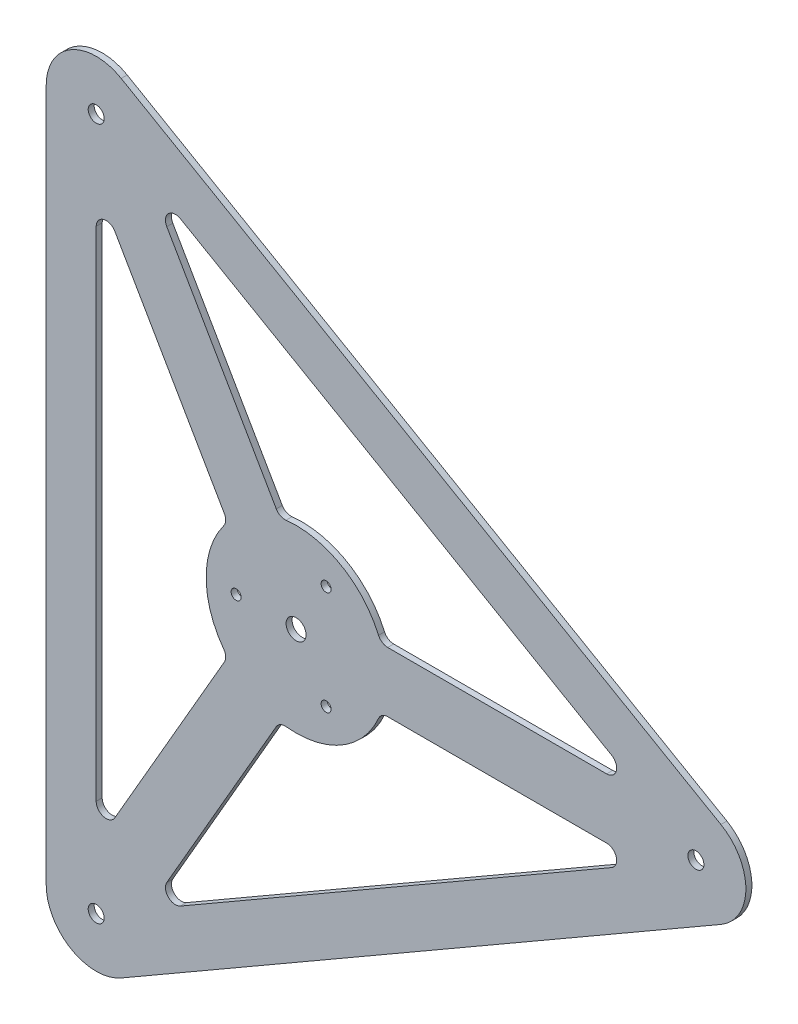
SolidWorks part; units mm, degrees
material "Hexcel AS4C (3000 Filaments)"
ref_plane "Front" through (0, 0, 0) normal (0, 0, 1) x (1, 0, 0)
ref_plane "Top" through (0, 0, 0) normal (0, 1, 0) x (1, 0, 0)
ref_plane "Right" through (0, 0, 0) normal (1, 0, 0) x (0, 0, -1)
sketch "BoardSke" plane through (0, 0, 0) normal (0, 0, 1) x (1, 0, 0)
  line L1 (42.5, 4.3301) -> (-17.5, 38.9711)
  line L2 (-25, 34.641) -> (-25, -34.641)
  line L3 (-17.5, -38.9711) -> (42.5, -4.3301)
  circle A0 centre (0, 0) radius 25 construction
  arc A1 (-25, -34.641) -> (-17.5, -38.9711) centre (-20, -34.641) ccw
  arc A2 (42.5, 4.3301) -> (42.5, -4.3301) centre (40, 0) cw
  arc A3 (-17.5, 38.9711) -> (-25, 34.641) centre (-20, 34.641) ccw
  dimension "D1" = 50
  dimension "D2" = 5
extrude "Board" add sketch "BoardSke" along normal blind 0.6 separate body
sketch "CutSke" plane through (0, 0, 0.6) normal (0, 0, 1) x (1, 0, 0)
  line L0 (31.0718, 3) -> (9.1652, 3)
  line L1 (31.5718, 4.866) -> (-11.5718, 29.775)
  line L2 (-12.9378, 28.409) -> (-1.9845, 9.4373)
  line L3 (0, 0) -> (-22.5, 38.9711) construction
  line L4 (0, 0) -> (45, 0) construction
  line L5 (0, 0) -> (-22.5, -38.9711) construction
  line L6 (42.5, 4.3301) -> (-17.5, 38.9711) construction
  line L7 (31.0718, -3) -> (9.1652, -3)
  line L8 (-11.5718, -29.775) -> (31.5718, -4.866)
  line L9 (-12.9378, -28.409) -> (-1.9845, -9.4373)
  line L10 (-18.134, -25.409) -> (-7.1807, -6.4373)
  line L11 (-20, 24.909) -> (-20, -24.909)
  line L12 (-18.134, 25.409) -> (-7.1807, 6.4373)
  arc A0 (8.2486, 3.6) -> (-1.0066, 8.9435) centre (0, 0) ccw
  arc A1 (-17.5, 38.9711) -> (-25, 34.641) centre (-20, 34.641) ccw construction
  arc A2 (42.5, -4.3301) -> (42.5, 4.3301) centre (40, 0) ccw construction
  arc A3 (-25, -34.641) -> (-17.5, -38.9711) centre (-20, -34.641) ccw construction
  arc A4 (31.0718, 3) -> (31.5718, 4.866) centre (31.0718, 4) ccw
  arc A5 (-11.5718, 29.775) -> (-12.9378, 28.409) centre (-12.0718, 28.909) ccw
  arc A6 (-1.9845, 9.4373) -> (-1.0066, 8.9435) centre (-1.1185, 9.9373) ccw
  arc A7 (9.1652, 3) -> (8.2486, 3.6) centre (9.1652, 4) cw
  arc A8 (-1.0066, -8.9435) -> (8.2486, -3.6) centre (0, 0) ccw
  arc A9 (-1.9845, -9.4373) -> (-1.0066, -8.9435) centre (-1.1185, -9.9373) cw
  arc A10 (9.1652, -3) -> (8.2486, -3.6) centre (9.1652, -4) ccw
  arc A11 (31.5718, -4.866) -> (31.0718, -3) centre (31.0718, -4) ccw
  arc A12 (-12.9378, -28.409) -> (-11.5718, -29.775) centre (-12.0718, -28.909) ccw
  arc A13 (-7.242, 5.3435) -> (-7.242, -5.3435) centre (0, 0) ccw
  arc A14 (-7.1807, 6.4373) -> (-7.242, 5.3435) centre (-8.0467, 5.9373) cw
  arc A15 (-7.1807, -6.4373) -> (-7.242, -5.3435) centre (-8.0467, -5.9373) ccw
  arc A16 (-20, -24.909) -> (-18.134, -25.409) centre (-19, -24.909) ccw
  arc A17 (-18.134, 25.409) -> (-20, 24.909) centre (-19, 24.909) ccw
  point P55 (0, 0)
  dimension "D1" = 18
  dimension "D5" = 1
  dimension "D6" = 1
  dimension "D2" = 3
  dimension "D3" = 3
  dimension "D4" = 5
  dimension "D7" = 3
extrude "Cut" cut sketch "CutSke" against normal through all
sketch "HolesSke" plane through (0, 0, 0.6) normal (0, 0, 1) x (1, 0, 0)
  circle A0 centre (-6, 0) radius 0.5
  circle A1 centre (3, 5.1962) radius 0.5
  circle A2 centre (3, -5.1962) radius 0.5
  circle A3 centre (0, 0) radius 1
  point P9 (0, 0)
  dimension "D2" = 6
  dimension "D1" = 1
  dimension "D4" = 2
  dimension "D3" = 3
extrude "Holes" cut sketch "HolesSke" against normal through all
sketch "Holes2Ske" plane through (0, 0, 0.6) normal (0, 0, 1) x (1, 0, 0)
  line L1 (0, 0) -> (40, 0) construction
  circle A2 centre (40, 0) radius 0.8
  circle A4 centre (-20, -34.641) radius 0.8
  circle A6 centre (-20, 34.641) radius 0.8
  point P18 (0, 0)
  dimension "D1" = 40
  dimension "D2" = 1.6
  dimension "D4" = 3
extrude "Holes2" cut sketch "Holes2Ske" against normal through all
